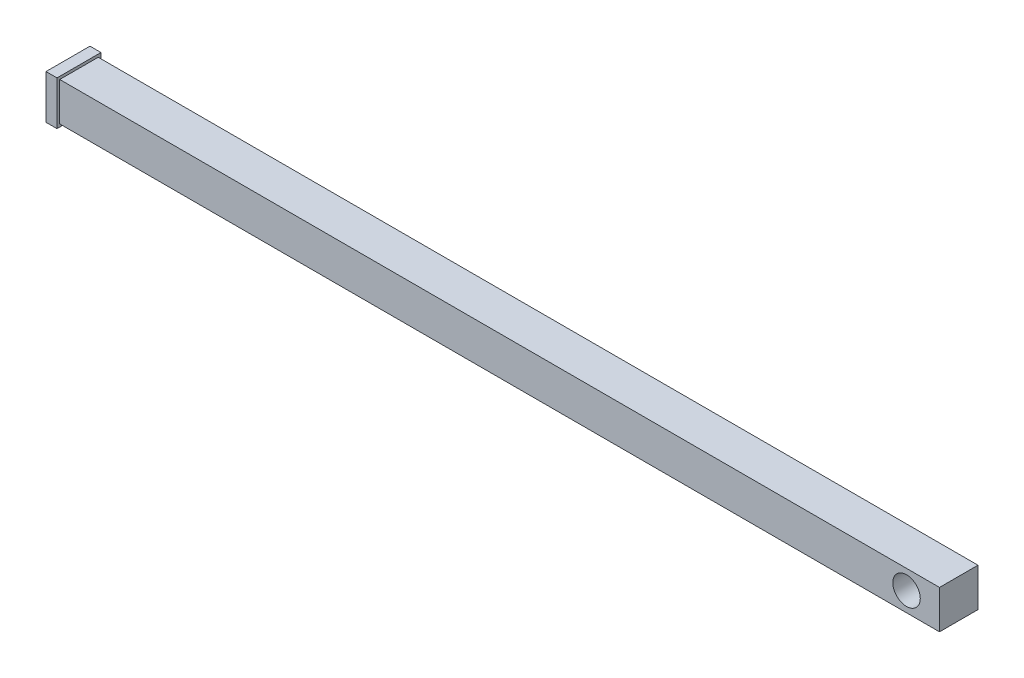
SolidWorks part; units mm, degrees
ref_plane "Plan de face" through (0, 0, 0) normal (0, 0, 1) x (1, 0, 0)
ref_plane "Plan de dessus" through (0, 0, 0) normal (0, 1, 0) x (1, 0, 0)
ref_plane "Plan de droite" through (0, 0, 0) normal (1, 0, 0) x (0, 0, -1)
sketch "Esquisse1" plane through (0, 0, 0) normal (1, 0, 0) x (0, 0, -1)
  line L1 (-17.5, 17.5) -> (17.5, 17.5)
  line L2 (-17.5, 17.5) -> (-17.5, -17.5)
  line L3 (-17.5, -17.5) -> (17.5, -17.5)
  line L4 (17.5, 17.5) -> (17.5, -17.5)
  line L5 (-17.5, 17.5) -> (17.5, -17.5) construction
  line L6 (-17.5, -17.5) -> (17.5, 17.5) construction
  point P0 (0, 0)
  dimension "D1" = 35
  dimension "D2" = 35
extrude "Boss.-Extru.1" add sketch "Esquisse1" along normal blind 800
sketch "Esquisse2" plane through (0, 0, 0) normal (-1, 0, 0) x (0, 0, 1)
  line L1 (-20, 20) -> (20, 20)
  line L2 (-20, 20) -> (-20, -20)
  line L3 (-20, -20) -> (20, -20)
  line L4 (-17.5, 17.5) -> (-17.5, -17.5)
  line L5 (-17.5, -17.5) -> (17.5, -17.5)
  line L6 (17.5, -17.5) -> (17.5, 17.5)
  line L7 (17.5, 17.5) -> (-17.5, 17.5)
  line L8 (-17.5, 17.5) -> (-17.5, -17.5)
  line L9 (-17.5, -17.5) -> (17.5, -17.5)
  line L10 (17.5, -17.5) -> (17.5, 17.5)
  line L11 (17.5, 17.5) -> (-17.5, 17.5)
  line L12 (20, 20) -> (20, -20)
  line L13 (-20, 20) -> (20, -20) construction
  line L14 (-20, -20) -> (20, 20) construction
  point P2 (0, 0)
  line M9 (-17.5, 17.5) -> (-17.5, -17.5)
  line M10 (-17.5, -17.5) -> (17.5, -17.5)
  line M11 (17.5, -17.5) -> (17.5, 17.5)
  line M12 (17.5, 17.5) -> (-17.5, 17.5)
  dimension "D2" = 40
  dimension "D3" = 40
  dimension "D1" = 0
extrude "Boss.-Extru.2" add sketch "Esquisse2" along normal blind 10 contours L12 L1 L2 L3 M9 M12 M11 M10 | M12 M9 M10 M11
sketch "Esquisse7" plane through (0, 0, 17.5) normal (0, 0, 1) x (1, 0, 0)
  line L0 (0, 0) -> (422.5989, 0) construction
  line L1 (770, 17.5) -> (770, -17.5) construction
  line L2 (800, 17.5) -> (0, 17.5) construction
  line L3 (800, -17.5) -> (0, -17.5) construction
  line L4 (800, 17.5) -> (800, -17.5) construction
  circle A0 centre (770, 0) radius 12.5
  dimension "D2" = 25
  dimension "D1" = 30
extrude "Enlèv. mat.-Extru.1" cut sketch "Esquisse7" against normal blind 25
